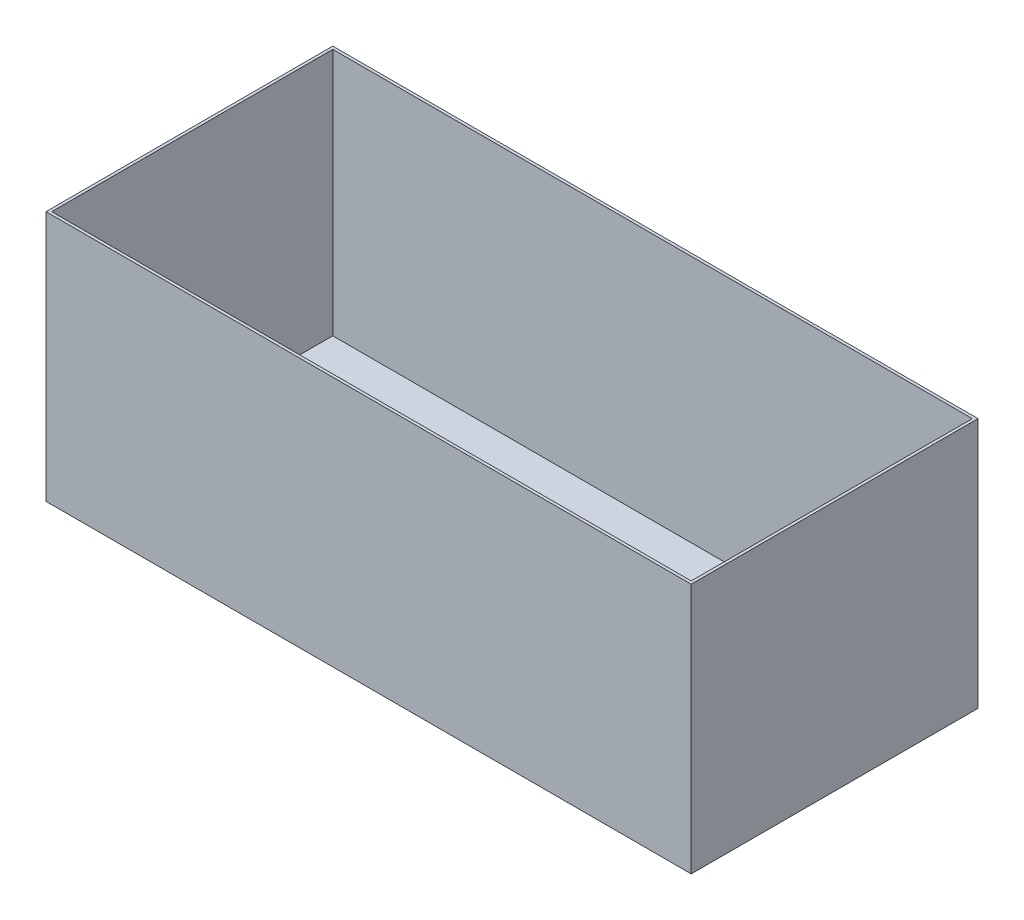
SolidWorks part; units mm, degrees
ref_plane "Front Plane" through (0, 0, 0) normal (0, 0, 1) x (1, 0, 0)
ref_plane "Top Plane" through (0, 0, 0) normal (0, 1, 0) x (1, 0, 0)
ref_plane "Right Plane" through (0, 0, 0) normal (1, 0, 0) x (0, 0, -1)
sketch "Sketch1" plane through (0, 0, 0) normal (0, 1, 0) x (1, 0, 0)
  line L1 (0, -8.4924) -> (228.6, -8.4924)
  line L2 (0, -8.4924) -> (0, 93.1076)
  line L3 (0, 93.1076) -> (228.6, 93.1076)
  line L4 (228.6, -8.4924) -> (228.6, 93.1076)
  dimension "D1" = 228.6
  dimension "D2" = 101.6
extrude "Boss-Extrude1" add sketch "Sketch1" along normal blind 88.9
shell "Shell1" thickness 1
